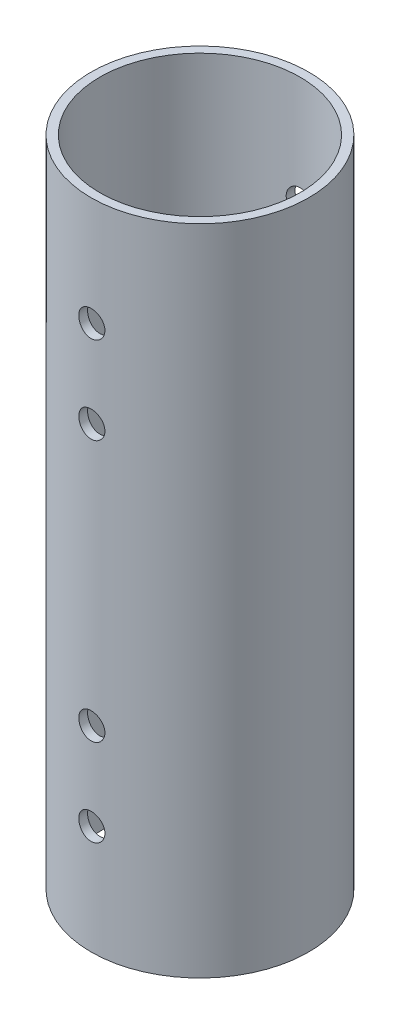
SolidWorks part; units mm, degrees
material "Thornel Mat VMA"
ref_plane "前视基准面" through (0, 0, 0) normal (0, 0, 1) x (1, 0, 0)
ref_plane "上视基准面" through (0, 0, 0) normal (0, 1, 0) x (1, 0, 0)
ref_plane "右视基准面" through (0, 0, 0) normal (1, 0, 0) x (0, 0, -1)
other "Configuration Table"
sketch "草图1" plane through (0, 0, 0) normal (0, 1, 0) x (1, 0, 0)
  circle A0 centre (0, 0) radius 25
  circle A1 centre (0, 0) radius 23
  dimension "D1" = 50
  dimension "D2" = 46
extrude "凸台-拉伸1" add sketch "草图1" along normal blind 150
sketch "草图3" plane through (0, 0, 0) normal (0, 0, 1) x (1, 0, 0)
  line L0 (-1014.7444, 75) -> (48985.2556, 75) construction
  line L1 (-25, 0) -> (25, 0) construction
  line L2 (-25, 150) -> (-25, 0) construction
  line L3 (25, 0) -> (-25, 0) construction
  line L4 (25, 0) -> (25, 70) construction
  line L5 (25, 70) -> (-25, 70) construction
  line L6 (-25, 0) -> (-25, 70) construction
  line L7 (25, 70) -> (-25, 0) construction
  line L8 (-25, 70) -> (25, 0) construction
  line L9 (0, 25) -> (0, 45) construction
  circle A0 centre (0, 45) radius 3
  circle A1 centre (0, 25) radius 3
  circle A2 centre (0, 125) radius 3
  circle A3 centre (0, 105) radius 3
  point P15 (0, 35)
  dimension "D4" = 6
  dimension "D5" = 6
  dimension "D1" = 75
  dimension "D2" = 70
  dimension "D3" = 20
extrude "切除-拉伸2" cut sketch "草图3" against normal through all and the other way through all
